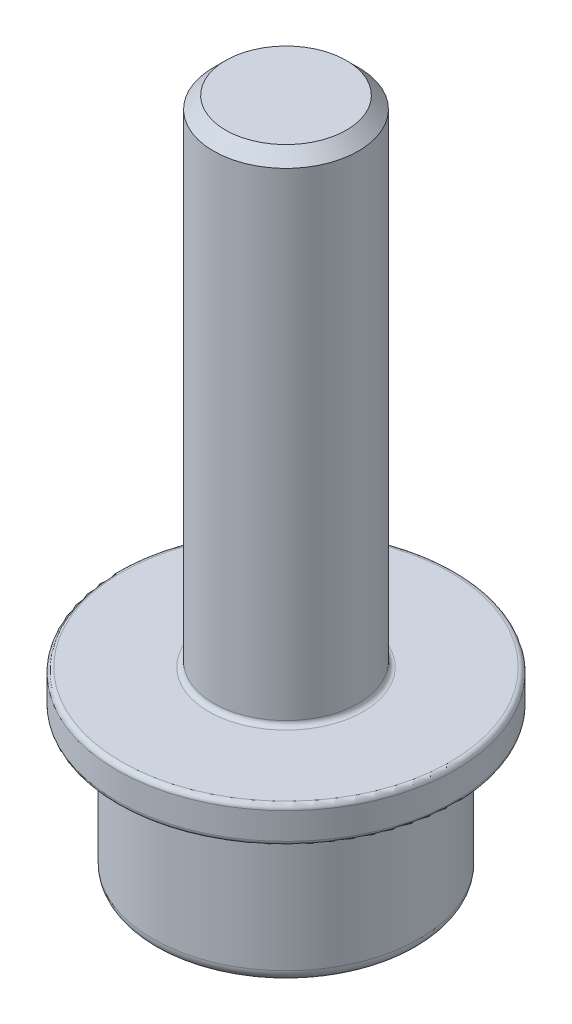
SolidWorks part; units mm, degrees
ref_plane "Front Plane" through (0, 0, 0) normal (0, 0, 1) x (1, 0, 0)
ref_plane "Top Plane" through (0, 0, 0) normal (0, 1, 0) x (1, 0, 0)
ref_plane "Right Plane" through (0, 0, 0) normal (1, 0, 0) x (0, 0, -1)
sketch "Sketch1" plane through (0, 0, 0) normal (0, 1, 0) x (1, 0, 0)
  circle A0 centre (0, 0) radius 2.75
  dimension "D1" = 5.5
extrude "Boss-Extrude1" add sketch "Sketch1" along normal blind 3
sketch "Sketch2" plane through (0, 3, 0) normal (0, 1, 0) x (1, 0, 0)
  circle A0 centre (0, 0) radius 1.5
  dimension "D1" = 3
extrude "Boss-Extrude2" add sketch "Sketch2" along normal blind 11 contours A0
sketch "Sketch3" plane through (0, 0, 0) normal (0, -1, 0) x (1, 0, 0)
  line L1 (0.9342, 0.9746) -> (-0.3769, 1.2963)
  line L2 (-0.3769, 1.2963) -> (-1.3111, 0.3217)
  line L3 (-1.3111, 0.3217) -> (-0.9342, -0.9746)
  line L4 (-0.9342, -0.9746) -> (0.3769, -1.2963)
  line L5 (0.3769, -1.2963) -> (1.3111, -0.3217)
  line L6 (1.3111, -0.3217) -> (0.9342, 0.9746)
  circle A0 centre (0, 0) radius 1.1691 construction
  dimension "D1" = 2.7
extrude "Cut-Extrude1" cut sketch "Sketch3" against normal blind 1.5
chamfer "Chamfer1" distance 0.25 distance2 0.25 6 edges at (-0.2786, 0, -1.1355) (-1.1226, 0, -0.3264) (-0.844, 0, 0.809) (0.2786, 0, 1.1355) (1.1226, 0, 0.3264) (0.844, 0, -0.809)
fillet "Fillet1" radius 0.25 1 edges at (0, 0, 2.75)
chamfer "Chamfer2" distance 0.25 angle 45 1 edges at (0, 14, 1.5)
fillet "Fillet2" radius 0.1 1 edges at (0, 3, 2.75)
sketch "Sketch4" plane through (0, 3, 0) normal (0, 1, 0) x (1, 0, 0)
  circle A0 centre (0, 0) radius 1.5
  circle A1 centre (0, 0) radius 3.5
  circle A2 centre (0, 0) radius 1.5 construction
  dimension "D1" = 7
extrude "Boss-Extrude3" add sketch "Sketch4" along normal blind 0.75
fillet "Fillet3" radius 0.1 3 edges at (0, 3.75, 1.5) (0, 3.75, 3.5) (0, 3, 3.5)
